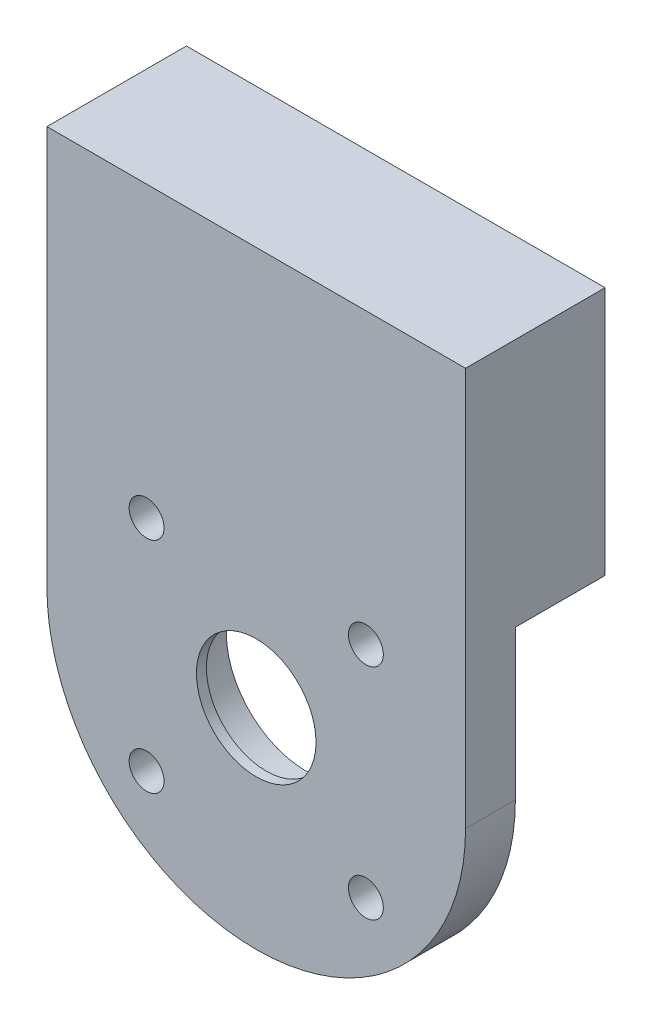
SolidWorks part; units mm, degrees
ref_plane "Front Plane" through (0, 0, 0) normal (0, 0, 1) x (1, 0, 0)
ref_plane "Top Plane" through (0, 0, 0) normal (0, 1, 0) x (1, 0, 0)
ref_plane "Right Plane" through (0, 0, 0) normal (1, 0, 0) x (0, 0, -1)
sketch "Sketch1" plane through (0, 0, 0) normal (0, 0, 1) x (1, 0, 0)
  line L1 (-21, 40) -> (21, 40)
  line L2 (-21, 40) -> (-21, 0)
  line L4 (21, 40) -> (21, 0)
  arc A0 (-21, 0) -> (21, 0) centre (0, 0) ccw
  dimension "D1" = 42
  dimension "D2" = 40
extrude "Boss-Extrude1" add sketch "Sketch1" along normal blind 5
sketch "Sketch2" plane through (0, 0, 5) normal (0, 0, 1) x (1, 0, 0)
  circle A0 centre (0, 0) radius 6
  dimension "D1" = 12
extrude "Cut-Extrude1" cut sketch "Sketch2" against normal through all
sketch "Sketch3" plane through (0, 0, 0) normal (0, 0, -1) x (-1, 0, 0)
  circle A0 centre (0, 0) radius 8
  dimension "D1" = 16
extrude "Cut-Extrude2" cut sketch "Sketch3" against normal blind 4
sketch "Sketch4" plane through (0, 0, 0) normal (0, 0, -1) x (-1, 0, 0)
  line L0 (0, -2.8223) -> (0, 0) construction
  line L1 (0, 0) -> (-2.4223, 0) construction
  circle A0 centre (-11, 11) radius 1.75
  circle A1 centre (-11, -11) radius 1.75
  circle A2 centre (11, -11) radius 1.75
  circle A3 centre (11, 11) radius 1.75
  dimension "D2" = 3.5
  dimension "D1" = 11
  dimension "D3" = 11
extrude "Cut-Extrude3" cut sketch "Sketch4" against normal through all
sketch "Sketch5" plane through (0, 0, 0) normal (0, 0, -1) x (-1, 0, 0)
  line L0 (0, -2.3811) -> (0, 0) construction
  line L1 (-11, 14.2909) -> (-13.85, 12.6454)
  line L2 (-13.85, 12.6454) -> (-13.85, 9.3546)
  line L3 (-13.85, 9.3546) -> (-11, 7.7091)
  line L4 (-11, 7.7091) -> (-8.15, 9.3546)
  line L5 (-8.15, 9.3546) -> (-8.15, 12.6454)
  line L6 (-8.15, 12.6454) -> (-11, 14.2909)
  line L7 (0, 0) -> (-2.8636, 0) construction
  line L8 (-8.15, -12.6454) -> (-11, -14.2909)
  line L9 (-8.15, -9.3546) -> (-8.15, -12.6454)
  line L10 (-11, -7.7091) -> (-8.15, -9.3546)
  line L11 (-13.85, -9.3546) -> (-11, -7.7091)
  line L12 (-13.85, -12.6454) -> (-13.85, -9.3546)
  line L13 (-11, -14.2909) -> (-13.85, -12.6454)
  line L14 (11, -14.2909) -> (13.85, -12.6454)
  line L15 (13.85, -12.6454) -> (13.85, -9.3546)
  line L16 (13.85, -9.3546) -> (11, -7.7091)
  line L17 (11, -7.7091) -> (8.15, -9.3546)
  line L18 (8.15, -9.3546) -> (8.15, -12.6454)
  line L19 (8.15, -12.6454) -> (11, -14.2909)
  line L20 (8.15, 12.6454) -> (11, 14.2909)
  line L21 (8.15, 9.3546) -> (8.15, 12.6454)
  line L22 (11, 7.7091) -> (8.15, 9.3546)
  line L23 (13.85, 9.3546) -> (11, 7.7091)
  line L24 (13.85, 12.6454) -> (13.85, 9.3546)
  line L25 (11, 14.2909) -> (13.85, 12.6454)
  circle A0 centre (-11, 11) radius 2.85 construction
  circle A1 centre (-11, -11) radius 2.85 construction
  circle A2 centre (11, -11) radius 2.85 construction
  circle A3 centre (11, 11) radius 2.85 construction
  dimension "D1" = 5.7
extrude "Cut-Extrude4" cut sketch "Sketch5" against normal blind 2
sketch "Sketch6" plane through (0, 0, 0) normal (0, 0, -1) x (-1, 0, 0)
  line L0 (21, 40) -> (21, 0) construction
  line L1 (-21, 40) -> (21, 40)
  line L2 (-21, 40) -> (-21, 15)
  line L3 (-21, 15) -> (21, 15)
  line L4 (21, 40) -> (21, 15)
  line L5 (-21, 40) -> (21, 15) construction
  line L6 (-21, 15) -> (21, 40) construction
  point P0 (0, 27.5)
  dimension "D1" = 25
  dimension "D2" = 15
extrude "Boss-Extrude2" add sketch "Sketch6" along normal blind 9
sketch "Sketch7" plane through (0, 0, 0) normal (0, 0, -1) x (-1, 0, 0)
  circle A0 centre (0, 0) radius 22
  dimension "D1" = 44
extrude "Cut-Extrude5" cut sketch "Sketch7" along normal through all
